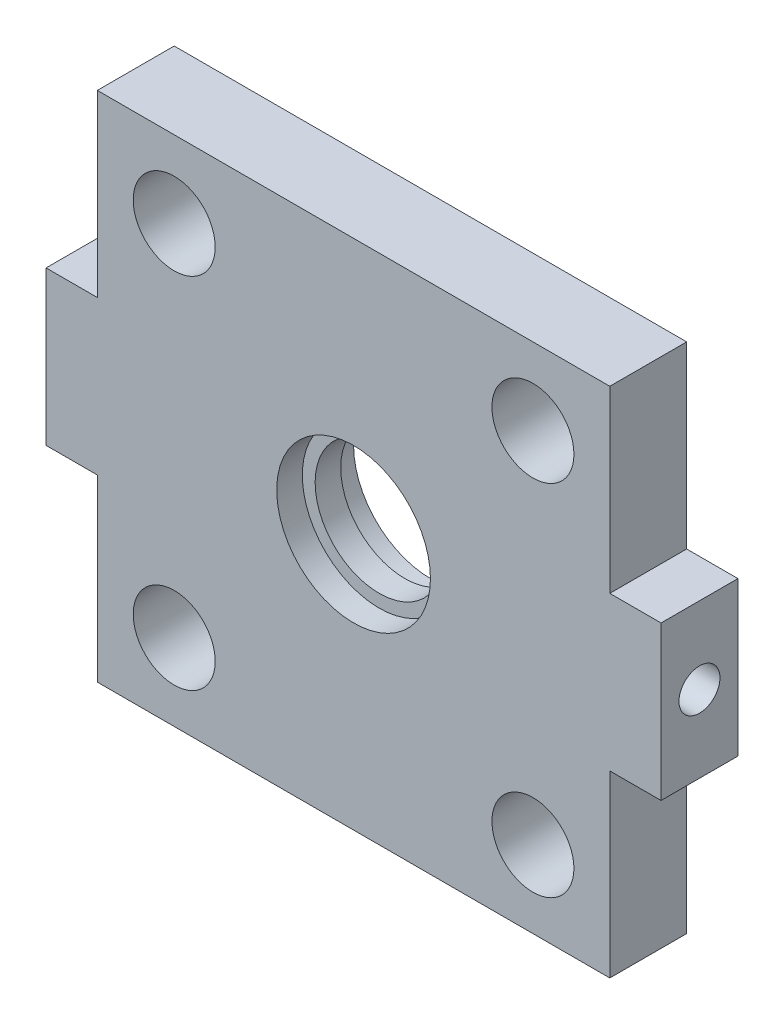
SolidWorks part; units mm, degrees
material "AISI 316 Annealed Stainless Steel Bar (SS)"
ref_plane "Front Plane" through (0, 0, 0) normal (0, 0, 1) x (1, 0, 0)
ref_plane "Top Plane" through (0, 0, 0) normal (0, 1, 0) x (1, 0, 0)
ref_plane "Right Plane" through (0, 0, 0) normal (1, 0, 0) x (0, 0, -1)
sketch "Sketch1" plane through (0, 0, 0) normal (0, 0, 1) x (1, 0, 0)
  line L1 (0, 0) -> (100, 0)
  line L2 (0, 0) -> (0, 100)
  line L3 (0, 100) -> (100, 100)
  line L4 (100, 0) -> (100, 100)
  circle A1 centre (15, 85) radius 8
  circle A2 centre (85, 85) radius 8
  circle A3 centre (85, 15) radius 8
  circle A4 centre (15, 15) radius 8
  dimension "D6" = 16
  dimension "D7" = 15
  dimension "D8" = 15
  dimension "D9" = 15
  dimension "D10" = 16
  dimension "D11" = 15
  dimension "D12" = 16
  dimension "D13" = 15
  dimension "D14" = 15
  dimension "D15" = 16
  dimension "D16" = 15
  dimension "D17" = 15
  dimension "D1" = 100
  dimension "D2" = 100
extrude "Boss-Extrude1" add sketch "Sketch1" along normal blind 15
sketch "Sketch4" plane through (100, 0, 0) normal (1, 0, 0) x (0, 0, -1)
  line L0 (-15, 0) -> (-15, 100) construction
  line L1 (-15, 65) -> (0, 65)
  line L2 (-15, 65) -> (-15, 35)
  line L3 (-15, 35) -> (0, 35)
  line L4 (0, 65) -> (0, 35)
  line L5 (0, 0) -> (0, 100) construction
  line L6 (-15, 100) -> (0, 100) construction
  dimension "D1" = 30
  dimension "D2" = 35
extrude "Boss-Extrude2" add sketch "Sketch4" along normal blind 10
sketch "Sketch7" plane through (0, 0, 0) normal (-1, 0, 0) x (0, 0, 1)
  line L0 (0, 100) -> (0, 0) construction
  line L1 (0, 65) -> (15, 65)
  line L2 (0, 65) -> (0, 35)
  line L3 (0, 35) -> (15, 35)
  line L4 (15, 65) -> (15, 35)
  line L5 (15, 100) -> (15, 0) construction
  line L6 (15, 100) -> (0, 100) construction
  dimension "D1" = 30
  dimension "D2" = 35
extrude "Boss-Extrude3" add sketch "Sketch7" along normal blind 10
sketch "Sketch8" plane through (0, 0, 15) normal (0, 0, 1) x (1, 0, 0)
  line L0 (0, 0) -> (100, 0) construction
  line L1 (110, 65) -> (110, 35) construction
  circle A0 centre (50, 50) radius 15
  dimension "D1" = 30
  dimension "D2" = 50
  dimension "D3" = 60
extrude "Cut-Extrude1" cut sketch "Sketch8" against normal blind 5
sketch "Sketch10" plane through (0, 0, 0) normal (0, 0, -1) x (-1, 0, 0)
  circle A1 centre (-50, 50) radius 15
  circle A2 centre (-50, 50) radius 15
  dimension "D1" = 0
extrude "Cut-Extrude2" cut sketch "Sketch10" against normal blind 5
sketch "Sketch11" plane through (0, 0, 0) normal (0, 0, -1) x (-1, 0, 0)
  circle A0 centre (-50, 50) radius 12.5
  dimension "D1" = 25
extrude "Cut-Extrude5" cut sketch "Sketch11" against normal through all
sketch "Sketch12" plane through (110, 0, 0) normal (1, 0, 0) x (0, 0, -1)
  line L0 (0, 65) -> (-15, 65) construction
  line L1 (-15, 65) -> (-15, 35) construction
  circle A0 centre (-7.5, 50) radius 4
  dimension "D1" = 8
  dimension "D2" = 15
  dimension "D3" = 7.5
extrude "Cut-Extrude6" cut sketch "Sketch12" against normal blind 20
sketch "Sketch13" plane through (-10, 0, 0) normal (-1, 0, 0) x (0, 0, 1)
  circle A1 centre (7.5, 50) radius 4
  circle A2 centre (7.5, 50) radius 4
  dimension "D1" = 0
extrude "Cut-Extrude7" cut sketch "Sketch13" against normal blind 20
